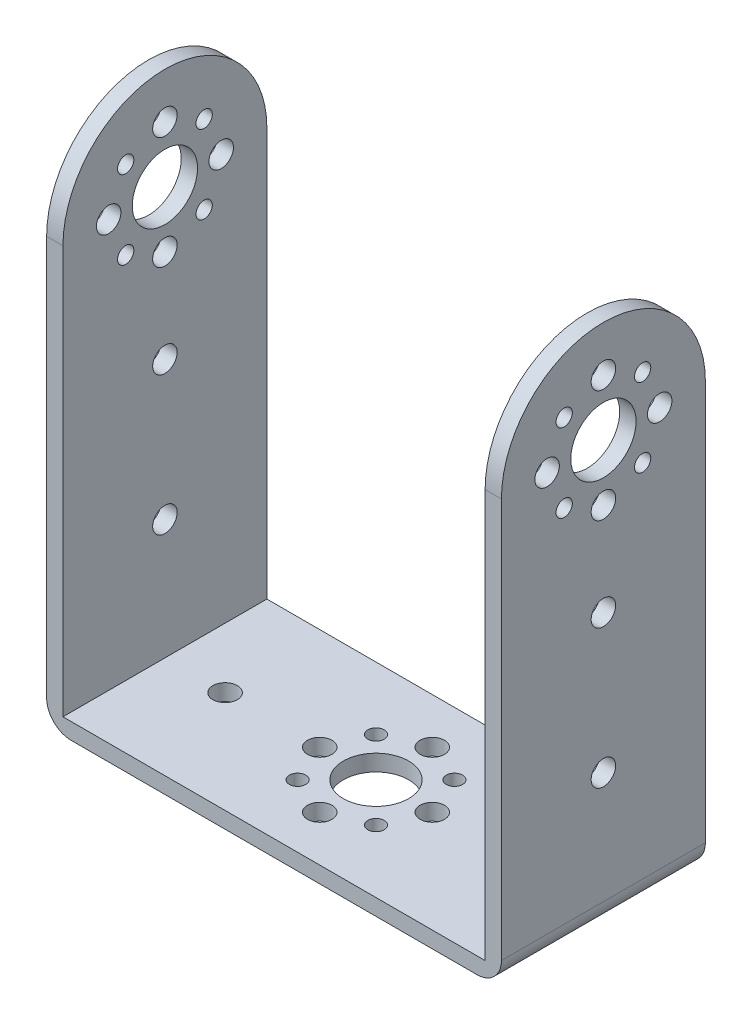
SolidWorks part; units mm, degrees
ref_plane "Front Plane" through (0, 0, 0) normal (0, 0, 1) x (1, 0, 0)
ref_plane "Top Plane" through (0, 0, 0) normal (0, 1, 0) x (1, 0, 0)
ref_plane "Right Plane" through (0, 0, 0) normal (1, 0, 0) x (0, 0, -1)
sketch "Sketch1" plane through (0, 0, 0) normal (0, 1, 0) x (1, 0, 0)
  line L0 (0, 0) -> (55.75, 0)
  line L1 (55.75, 0) -> (55.75, 25)
  line L2 (55.75, 25) -> (0, 25)
  line L3 (0, 25) -> (0, 0)
  line L4 (27.875, 25) -> (27.875, 0) construction
  line L5 (0, 12.5) -> (55.75, 12.5) construction
  line L6 (15.375, 0) -> (40.375, 25) construction
  line L7 (40.375, 0) -> (15.375, 25) construction
  line L8 (27.875, 16.5) -> (27.875, 19.4) construction
  line L9 (30.7034, 15.3284) -> (32.6833, 17.3083) construction
  line L10 (27.875, 12.5) -> (46.375, 12.5) construction
  circle A0 centre (27.875, 12.5) radius 4
  circle A1 centre (27.875, 19.4) radius 1.5
  circle A2 centre (34.775, 12.5) radius 1.5
  circle A3 centre (27.875, 5.6) radius 1.5
  circle A4 centre (20.975, 12.5) radius 1.5
  circle A5 centre (32.6833, 17.3083) radius 1
  circle A6 centre (32.6833, 7.6917) radius 1
  circle A7 centre (23.0667, 7.6917) radius 1
  circle A8 centre (23.0667, 17.3083) radius 1
  circle A9 centre (46.375, 12.5) radius 1.5
  circle A10 centre (9.375, 12.5) radius 1.5
  point P27 (27.875, 12.5)
  point P37 (27.875, 12.5)
  dimension "D1" = 4
  dimension "D2" = 4
extrude "Boss-Extrude1" add sketch "Sketch1" along normal blind 2
sketch "Sketch2" plane through (0, 2, 0) normal (0, 1, 0) x (1, 0, 0)
  line L0 (0, 0) -> (0, 25)
  line L1 (0, 25) -> (2, 25)
  line L2 (55.75, 25) -> (0, 25) construction
  line L3 (2, 25) -> (2, 0)
  line L4 (0, 0) -> (55.75, 0) construction
  line L5 (2, 0) -> (0, 0)
  line L6 (55.75, 25) -> (55.75, 0)
  line L7 (55.75, 0) -> (55.75, 25) construction
  line L8 (55.75, 0) -> (53.75, 0)
  line L9 (53.75, 0) -> (53.75, 25)
  line L10 (53.75, 25) -> (55.75, 25)
extrude "Boss-Extrude2" add sketch "Sketch2" along normal blind 62.5
fillet "Fillet1" radius 3 2 edges at (0, 0, -12.5) (55.75, 0, -12.5)
sketch "Sketch3" plane through (55.75, 0, 0) normal (1, 0, 0) x (0, 0, -1)
  line L0 (12.5, 64.5) -> (12.5, 3) construction
  line L1 (0, 64.5) -> (25, 64.5) construction
  line L2 (0, 3) -> (25, 3) construction
  line L3 (12.5, 64.5) -> (12.5, 52) construction
  line L4 (0, 64.5) -> (25, 64.5)
  line L5 (0, 52) -> (0, 64.5)
  line L6 (25, 64.5) -> (25, 52)
  arc A0 (25, 52) -> (0, 52) centre (12.5, 52) ccw
  line M2 (0, 64.5) -> (0, 3)
  line M4 (25, 3) -> (25, 64.5)
  line M5 (25, 64.5) -> (0, 64.5)
extrude "Cut-Extrude1" cut sketch "Sketch3" against normal blind 56 contours A0 L4 M2 | A0 M4 M5
sketch "Sketch4" plane through (55.75, 0, 0) normal (1, 0, 0) x (0, 0, -1)
  line L0 (12.5, 64.5) -> (12.5, 3) construction
  line L1 (0, 3) -> (25, 3) construction
  line L2 (0, 52) -> (25, 52) construction
  line L3 (0, 39.5) -> (21.3388, 60.8388) construction
  line L4 (25, 39.5) -> (3.6612, 60.8388) construction
  line L5 (25, 52) -> (25, 3) construction
  line L6 (0, 52) -> (0, 3) construction
  line L7 (25, 52) -> (25, 3)
  line L8 (0, 52) -> (0, 3)
  line L9 (16.5, 52) -> (19.4, 52) construction
  line L10 (15.3284, 54.8284) -> (17.3083, 56.8083) construction
  line L11 (12.5, 52) -> (12.5, 33.7) construction
  line L12 (12.5, 33.7) -> (12.5, 16.7) construction
  circle A0 centre (12.5, 52) radius 4
  arc A1 (25, 52) -> (0, 52) centre (12.5, 52) ccw construction
  arc A2 (25, 52) -> (0, 52) centre (12.5, 52) ccw
  circle A3 centre (19.4, 52) radius 1.5
  circle A4 centre (17.3083, 56.8083) radius 1
  circle A5 centre (17.3083, 47.1917) radius 1
  circle A6 centre (12.5, 45.1) radius 1.5
  circle A7 centre (7.6917, 47.1917) radius 1
  circle A8 centre (5.6, 52) radius 1.5
  circle A9 centre (7.6917, 56.8083) radius 1
  circle A10 centre (12.5, 58.9) radius 1.5
  circle A11 centre (12.5, 33.7) radius 1.5
  circle A12 centre (12.5, 16.7) radius 1.5
  point P38 (12.5, 52)
  dimension "D1" = 4
  dimension "D2" = 30.8
extrude "Cut-Extrude2" cut sketch "Sketch4" against normal blind 56 contours A0 | A8 | A10 | A3 | A6 | A7 | A11 | A12 | A9 | A4 | A5
